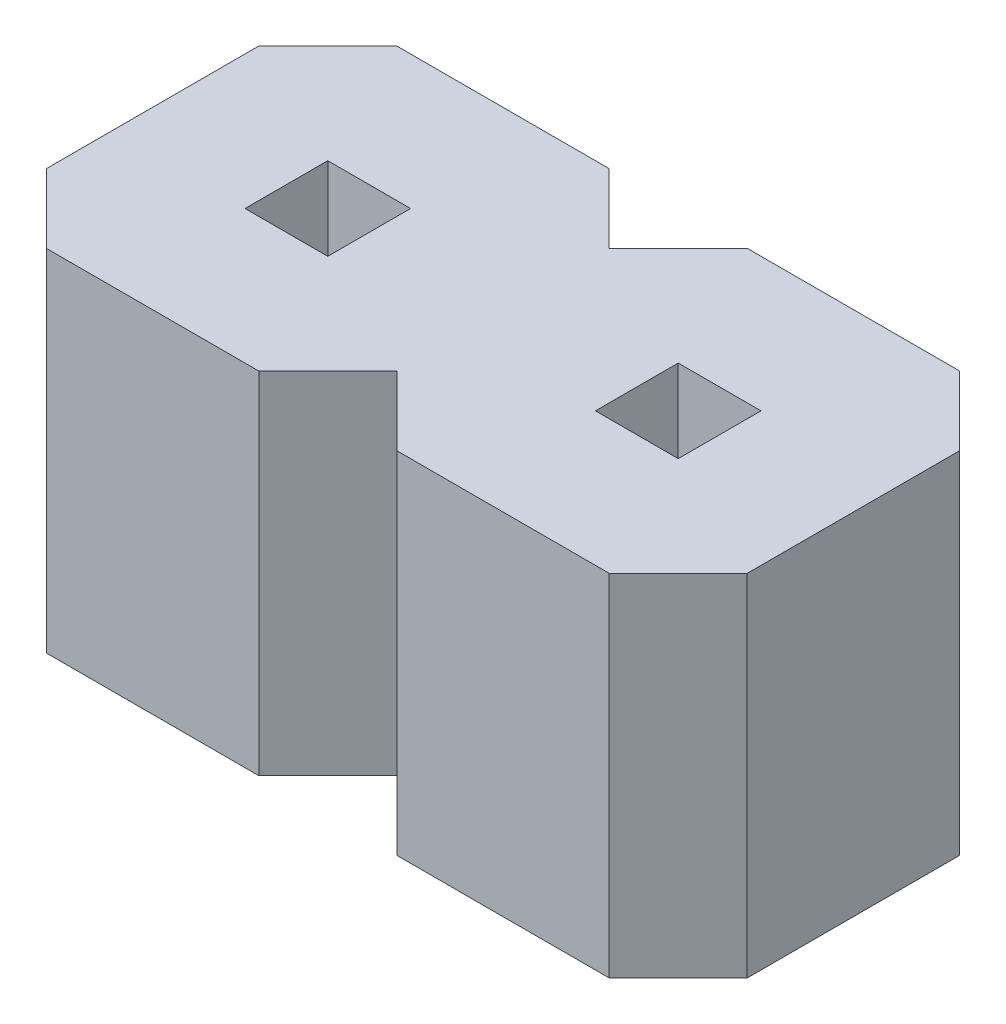
SolidWorks part; units mm, degrees
ref_plane "Спереди" through (0, 0, 0) normal (0, 0, 1) x (1, 0, 0)
ref_plane "Сверху" through (0, 0, 0) normal (0, 1, 0) x (1, 0, 0)
ref_plane "Справа" through (0, 0, 0) normal (1, 0, 0) x (0, 0, -1)
sketch "Sketch1" plane through (0, 0, 0) normal (0, 1, 0) x (1, 0, 0)
  line L0 (-5.08, 1.27) -> (0, 1.27) construction
  line L1 (-0.5, 0) -> (-2.04, 0)
  line L2 (0, 2.04) -> (0, 0.5)
  line L3 (-0.5, 2.54) -> (-2.04, 2.54)
  line L4 (-5.08, 0.5) -> (-5.08, 2.04)
  line L5 (-4.58, 2.54) -> (-5.08, 2.04)
  line L6 (-4.11, 0.97) -> (-3.51, 0.97)
  line L7 (-4.11, 0.97) -> (-4.11, 1.57)
  line L8 (-4.11, 1.57) -> (-3.51, 1.57)
  line L9 (-3.51, 0.97) -> (-3.51, 1.57)
  line L10 (-4.11, 0.97) -> (-3.51, 1.57) construction
  line L11 (-4.11, 1.57) -> (-3.51, 0.97) construction
  line L12 (-1.57, 0.97) -> (-0.97, 0.97)
  line L13 (-1.57, 0.97) -> (-1.57, 1.57)
  line L14 (-1.57, 1.57) -> (-0.97, 1.57)
  line L15 (-0.97, 0.97) -> (-0.97, 1.57)
  line L16 (-1.57, 0.97) -> (-0.97, 1.57) construction
  line L17 (-1.57, 1.57) -> (-0.97, 0.97) construction
  line L18 (-4.58, 0) -> (-5.08, 0.5)
  line L19 (0, 0.5) -> (-0.5, 0)
  line L20 (0, 2.04) -> (-0.5, 2.54)
  line L21 (-2.54, 2.54) -> (-2.54, 0) construction
  line L22 (-2.54, 0.5) -> (-2.04, 0)
  line L23 (-3.04, 2.54) -> (-2.54, 2.04)
  line L24 (-2.54, 2.04) -> (-2.04, 2.54)
  line L25 (-3.04, 0) -> (-2.54, 0.5)
  line L26 (-3.04, 2.54) -> (-4.58, 2.54)
  line L27 (-3.04, 0) -> (-4.58, 0)
  point P0 (0, 0)
  point P1 (-5.08, 2.54)
  point P2 (0, 2.54)
  point P3 (-5.08, 0)
  point P7 (-3.81, 1.27)
  point P12 (-1.27, 1.27)
  dimension "D1" = 0.6
  dimension "D2" = 0.6
  dimension "D3" = 0.6
  dimension "D4" = 0.6
  dimension "D5" = 2.54
  dimension "D6" = 2.54
  dimension "D7" = 5.08
  dimension "D9" = 1
  dimension "D10" = 0.5
  dimension "D15" = 0.5
  dimension "D16" = 1.54
extrude "Boss-Extrude1" add sketch "Sketch1" along normal blind 2.54
